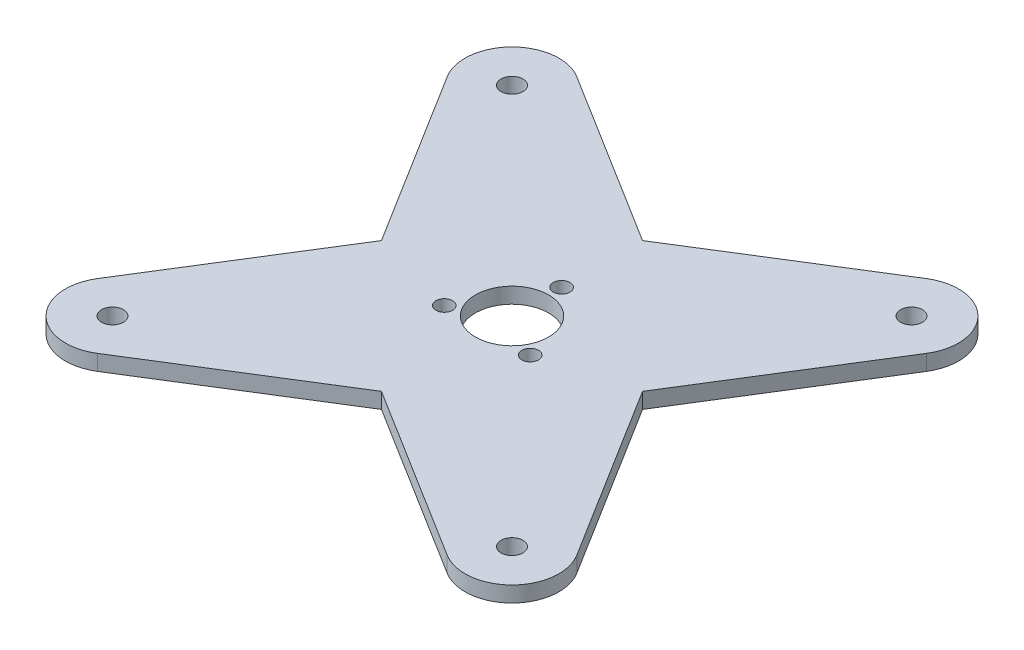
SolidWorks part; units mm, degrees
ref_plane "前视基准面" through (0, 0, 0) normal (0, 0, 1) x (1, 0, 0)
ref_plane "上视基准面" through (0, 0, 0) normal (0, 1, 0) x (1, 0, 0)
ref_plane "右视基准面" through (0, 0, 0) normal (1, 0, 0) x (0, 0, -1)
other "Configuration Table"
sketch "草图1" plane through (0, 0, 0) normal (0, 1, 0) x (1, 0, 0)
  line L0 (-159.9013, 0) -> (195.4814, 0) construction
  line L1 (-38.25, -38.25) -> (38.25, -38.25) construction
  line L2 (-38.25, -38.25) -> (-38.25, 38.25) construction
  line L3 (-38.25, 38.25) -> (38.25, 38.25) construction
  line L4 (38.25, -38.25) -> (38.25, 38.25) construction
  line L5 (-38.25, -38.25) -> (38.25, 38.25) construction
  line L6 (-38.25, 38.25) -> (38.25, -38.25) construction
  line L7 (0, 182.3675) -> (0, -172.8852) construction
  line L8 (-45.8864, 33.4871) -> (-25, 0)
  line L9 (-33.4871, 45.8864) -> (0, 25)
  line L10 (45.8864, 33.4871) -> (25, 0)
  line L11 (33.4871, 45.8864) -> (0, 25)
  line L12 (33.4871, -45.8864) -> (0, -25)
  line L13 (45.8864, -33.4871) -> (25, 0)
  line L14 (-45.8864, -33.4871) -> (-25, 0)
  line L15 (-33.4871, -45.8864) -> (0, -25)
  circle A0 centre (0, 0) radius 54.0937 construction
  circle A1 centre (38.25, 38.25) radius 2.1
  circle A2 centre (-38.25, -38.25) radius 2.1
  circle A3 centre (38.25, -38.25) radius 2.1
  circle A4 centre (-38.25, 38.25) radius 2.1
  arc A5 (-33.4871, 45.8864) -> (-45.8864, 33.4871) centre (-38.25, 38.25) ccw
  arc A6 (45.8864, 33.4871) -> (33.4871, 45.8864) centre (38.25, 38.25) ccw
  arc A7 (33.4871, -45.8864) -> (45.8864, -33.4871) centre (38.25, -38.25) ccw
  arc A8 (-45.8864, -33.4871) -> (-33.4871, -45.8864) centre (-38.25, -38.25) ccw
  point P41 (0, 0)
  dimension "D3" = 4.2
  dimension "D4" = 4.2
  dimension "D5" = 4.2
  dimension "D6" = 4.2
  dimension "D7" = 18
  dimension "D1" = 76.5
  dimension "D2" = 76.5
  dimension "D8" = 25
  dimension "D9" = 4
extrude "凸台-拉伸1" add sketch "草图1" along normal blind 3
sketch "草图2" plane through (0, 3, 0) normal (0, 1, 0) x (1, 0, 0)
  line L0 (0, 39.3455) -> (0, -51.5467) construction
  circle A0 centre (0, 0) radius 7
  circle A1 centre (0, 0) radius 9.5 construction
  circle A2 centre (0, 9.5) radius 1.6
  circle A3 centre (8.2272, -4.75) radius 1.6
  circle A4 centre (-8.2272, -4.75) radius 1.6
  point P8 (11.0038, -3.4929)
  point P15 (0, 0)
  dimension "D1" = 14
  dimension "D2" = 19
  dimension "D3" = 3.2
  dimension "D4" = 3
extrude "切除-拉伸1" cut sketch "草图2" against normal blind 10
